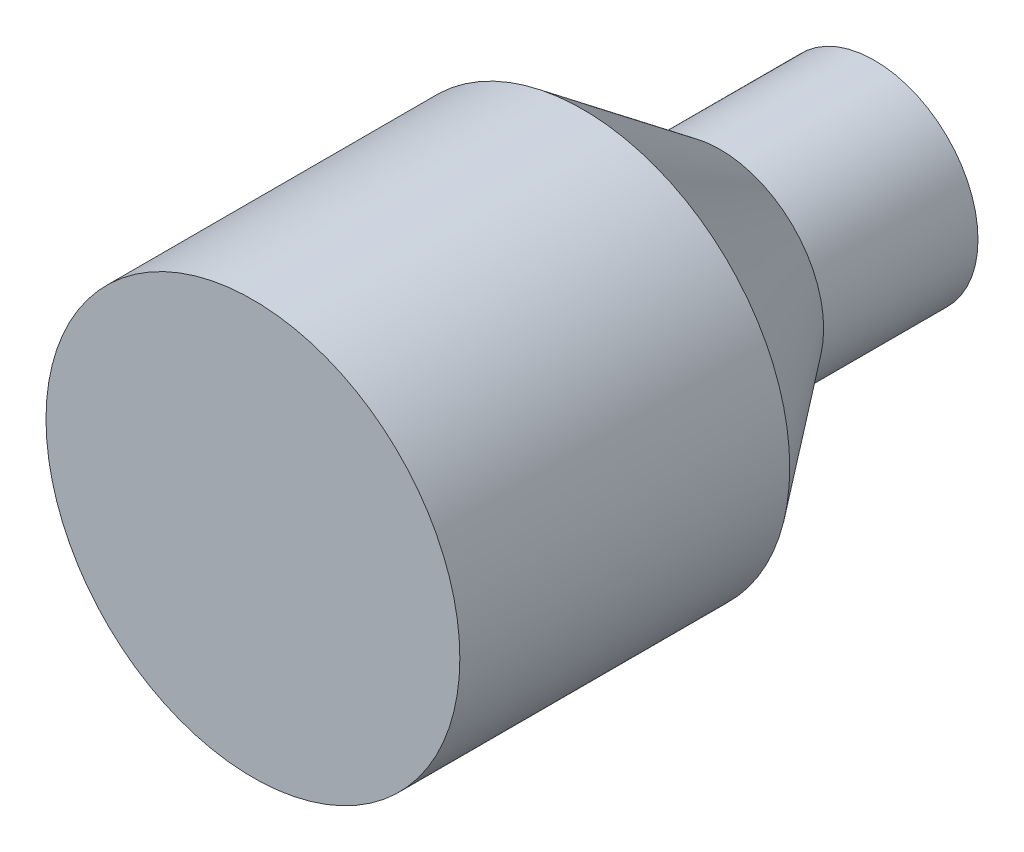
SolidWorks part; units mm, degrees
material "Plain Carbon Steel"
ref_plane "Front Plane" through (0, 0, 0) normal (0, 0, 1) x (1, 0, 0)
ref_plane "Top Plane" through (0, 0, 0) normal (0, 1, 0) x (1, 0, 0)
ref_plane "Right Plane" through (0, 0, 0) normal (1, 0, 0) x (0, 0, -1)
sketch "Sketch1" plane through (0, 0, 0) normal (0, 1, 0) x (1, 0, 0)
  line L0 (0, 0) -> (0, 89.9909) construction
  line L1 (0, 0) -> (33.626, 0)
  line L2 (33.626, 0) -> (33.626, 53.6087)
  line L3 (33.626, 53.6087) -> (16.813, 75.9341)
  line L4 (16.813, 75.9341) -> (16.813, 101.0158)
  line L5 (16.813, 101.0158) -> (0, 101.0158)
  line L6 (0, 0) -> (0, 101.0158)
revolve "Revolve1" add sketch "Sketch1" angle 360 about L6
